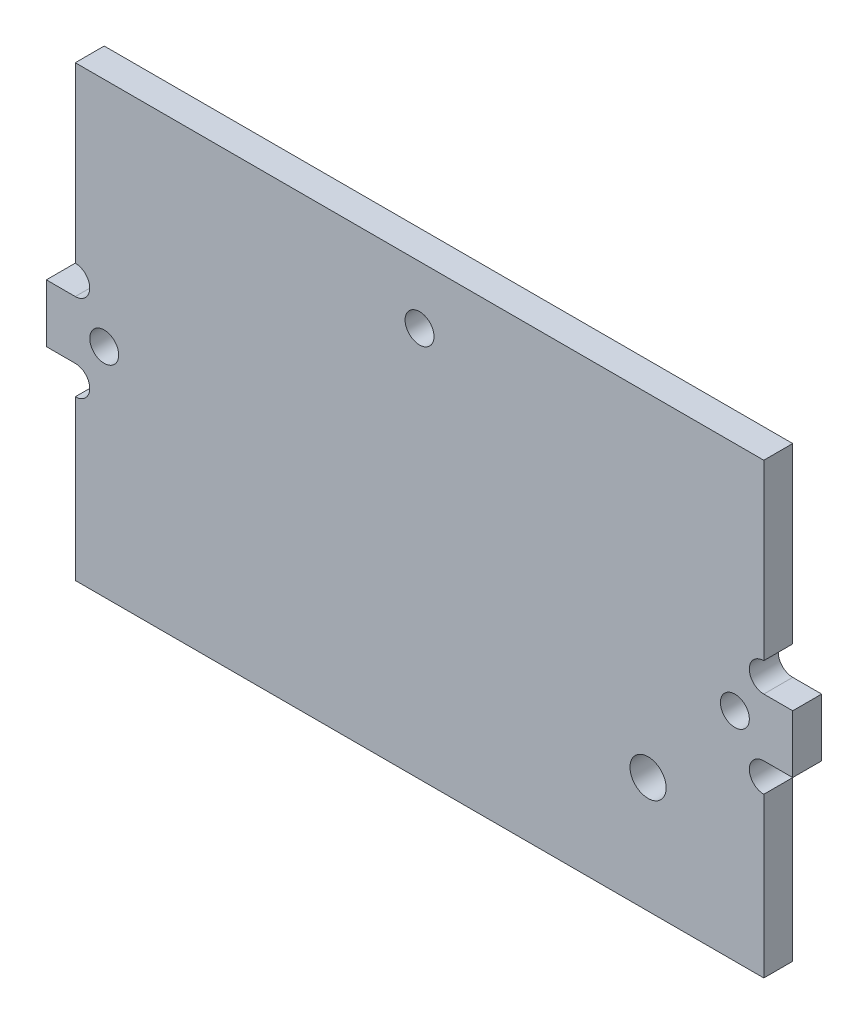
SolidWorks part; units mm, degrees
material "自訂玻璃纖維"
ref_plane "前基準面" through (0, 0, 0) normal (0, 0, 1) x (1, 0, 0)
ref_plane "上基準面" through (0, 0, 0) normal (0, 1, 0) x (1, 0, 0)
ref_plane "右基準面" through (0, 0, 0) normal (1, 0, 0) x (0, 0, -1)
sketch "草圖1" plane through (0, 0, 0) normal (0, 0, 1) x (1, 0, 0)
  line L0 (18.0581, -13.118) -> (-27.5419, -13.118)
  line L1 (-28.5419, 9.882) -> (-28.5419, 10.882)
  line L2 (-28.5419, 9.882) -> (-28.5419, 5.882)
  line L3 (-27.5419, 17.882) -> (-28.5419, 17.882)
  line L4 (19.0581, 9.882) -> (19.0581, 5.882)
  line L5 (19.0581, 10.882) -> (19.0581, 9.882)
  line L6 (-28.5419, 10.882) -> (-28.5419, 16.882)
  line L7 (-27.5419, 17.882) -> (18.0581, 17.882)
  line L8 (19.0581, 16.882) -> (19.0581, 10.882)
  line L9 (-28.5419, 17.882) -> (-28.5419, 16.882)
  line L10 (18.0581, 17.882) -> (19.0581, 17.882)
  line L11 (19.0581, 17.882) -> (19.0581, 16.882)
  line L12 (19.0581, -12.118) -> (19.0581, -13.118)
  line L13 (19.0581, -13.118) -> (18.0581, -13.118)
  line L14 (-28.5419, -12.118) -> (-28.5419, -13.118)
  line L15 (-28.5419, -13.118) -> (-27.5419, -13.118)
  line L16 (-28.5419, -2.118) -> (-28.5419, -12.118)
  line L17 (-28.5419, 3.882) -> (-30.5419, 3.882)
  line L18 (19.0581, -2.118) -> (19.0581, -12.118)
  line L19 (-28.5419, -0.118) -> (-30.5419, -0.118)
  line L20 (-30.5419, 3.882) -> (-30.5419, -0.118)
  line L21 (21.0581, 3.882) -> (21.0581, -0.118)
  line L22 (19.0581, -0.118) -> (21.0581, -0.118)
  line L23 (19.0581, 3.882) -> (21.0581, 3.882)
  arc A0 (-28.5419, 3.882) -> (-28.5419, 5.882) centre (-28.5419, 4.882) ccw
  circle A1 centre (11.0581, -5.118) radius 1.25
  arc A2 (-28.5419, -0.118) -> (-28.5419, -2.118) centre (-28.5419, -1.118) cw
  arc A3 (19.0581, -0.118) -> (19.0581, -2.118) centre (19.0581, -1.118) ccw
  arc A4 (19.0581, 3.882) -> (19.0581, 5.882) centre (19.0581, 4.882) cw
  circle A14 centre (-26.5419, 1.882) radius 1
  circle A15 centre (17.0581, 1.882) radius 1
  circle A16 centre (-4.7419, 13.882) radius 1
  point P6 (-28.5419, -13.118)
  point P13 (-28.5419, 17.882)
  point P25 (-8.5419, -13.118)
  point P31 (19.0581, 10.882)
  point P34 (-28.5419, 10.882)
  point P37 (-28.5419, 11.882)
  dimension "D3" = 2
  dimension "D4" = 2.5
  dimension "D5" = 8
  dimension "D6" = 8
  dimension "D8" = 4
  dimension "D7" = 4
  dimension "D10" = 23
  dimension "D11" = 2
  dimension "D14" = 2
  dimension "D15" = 2
  dimension "D1" = 47.6
  dimension "D2" = 7
  dimension "D9" = 2
extrude "填料-伸長2" add sketch "草圖1" along normal blind 2
